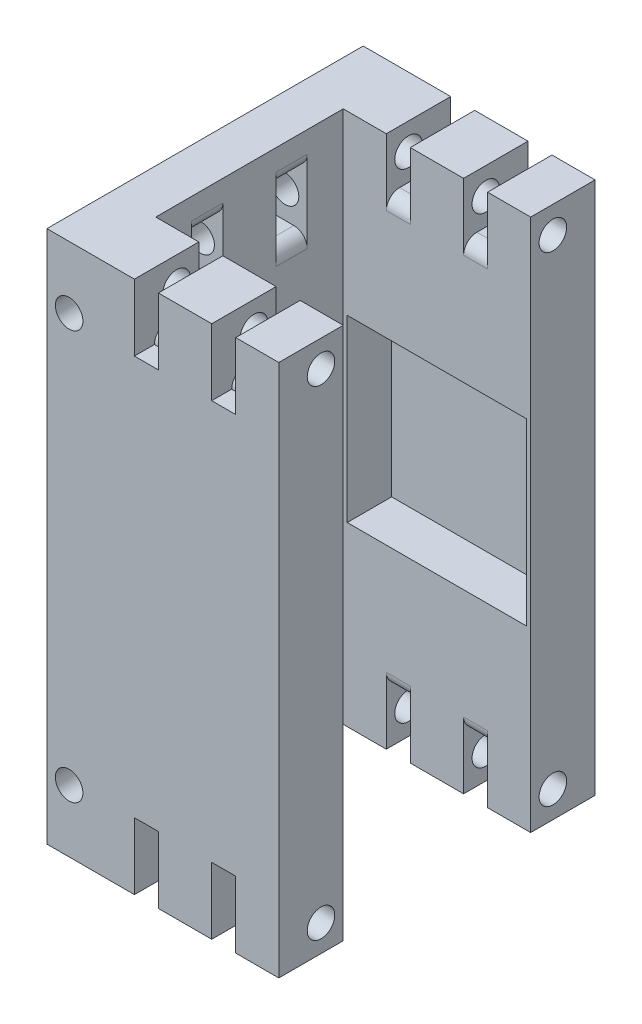
SolidWorks part; units mm, degrees
material "C (石墨)"
ref_plane "前视基准面" through (0, 0, 0) normal (0, 0, 1) x (1, 0, 0)
ref_plane "上视基准面" through (0, 0, 0) normal (0, 1, 0) x (1, 0, 0)
ref_plane "右视基准面" through (0, 0, 0) normal (1, 0, 0) x (0, 0, -1)
other "Configuration Table"
sketch "草图1" plane through (0, 0, 0) normal (0, 1, 0) x (1, 0, 0)
  line L0 (-5, -5) -> (26.1, -5)
  line L1 (0, 0) -> (21.1, 0)
  line L2 (0, 0) -> (0, 21.1)
  line L3 (0, 21.1) -> (21.1, 21.1)
  line L4 (21.1, 0) -> (21.1, 21.1)
  line L5 (26.1, -5) -> (26.1, 26.1)
  line L6 (-5, 26.1) -> (26.1, 26.1)
  line L7 (-5, -5) -> (-5, 26.1)
  dimension "D1" = 21.1
  dimension "D2" = 21.1
  dimension "D3" = 5
extrude "凸台-拉伸1" add sketch "草图1" along normal blind 60
sketch "草图2" plane through (-5, 0, 0) normal (-1, 0, 0) x (0, 0, 1)
  line L0 (-26.1, 60) -> (-26.1, 0) construction
  line L1 (-21.1, 60) -> (-21.1, 0) construction
  line L2 (-26.1, 60) -> (-26.1, 0) construction
  line L3 (-21.1, 60) -> (-21.1, 0) construction
  line L4 (-23.6, 60) -> (-23.6, 0) construction
  line L5 (-26.1, 60) -> (5, 60) construction
  line L6 (-26.1, 0) -> (5, 0) construction
  line L7 (-10.55, 60) -> (-10.55, 0) construction
  circle A0 centre (-23.6, 57) radius 1.55
  circle A1 centre (-23.6, 3) radius 1.55
  circle A2 centre (2.5, 3) radius 1.55
  circle A3 centre (2.5, 57) radius 1.55
  dimension "D4" = 3.1
  dimension "D1" = 2.5
  dimension "D2" = 3
  dimension "D3" = 3
extrude "切除-拉伸1" cut sketch "草图2" against normal through all
sketch "草图3" plane through (0, 0, -21.1) normal (0, 0, 1) x (1, 0, 0)
  line L0 (10.55, 60) -> (10.55, 0) construction
  line L1 (26.1, 30) -> (-5, 30) construction
  line L2 (4.85, 60) -> (7.55, 60)
  line L3 (4.85, 60) -> (4.85, 54)
  line L4 (0, 0) -> (21.1, 0)
  line L5 (21.1, 0) -> (21.1, 60)
  line L6 (21.1, 60) -> (0, 60)
  line L7 (0, 60) -> (0, 0)
  line L8 (0, 0) -> (21.1, 0) construction
  line L9 (21.1, 0) -> (21.1, 60) construction
  line L10 (21.1, 60) -> (0, 60) construction
  line L11 (0, 60) -> (0, 0) construction
  line L12 (4.85, 54) -> (7.55, 54)
  line L13 (7.55, 60) -> (7.55, 54)
  line L14 (13.55, 60) -> (16.25, 60)
  line L15 (13.55, 60) -> (13.55, 54)
  line L16 (13.55, 54) -> (16.25, 54)
  line L17 (16.25, 60) -> (16.25, 54)
  line L18 (26.1, 60) -> (26.1, 0) construction
  line L19 (-5, 60) -> (-5, 0) construction
  line L20 (16.25, 0) -> (16.25, 6)
  line L21 (13.55, 6) -> (16.25, 6)
  line L22 (13.55, 0) -> (13.55, 6)
  line L23 (13.55, 0) -> (16.25, 0)
  line L24 (7.55, 0) -> (7.55, 6)
  line L25 (4.85, 6) -> (7.55, 6)
  line L26 (4.85, 0) -> (4.85, 6)
  line L27 (4.85, 0) -> (7.55, 0)
  dimension "D2" = 6
  dimension "D3" = 2.7
  dimension "D4" = 3
  dimension "D1" = 0
extrude "切除-拉伸2" cut sketch "草图3" against normal through all and the other way through all
sketch "草图4" plane through (0, 0, -26.1) normal (0, 0, -1) x (-1, 0, 0)
  line L0 (-23.6, 60) -> (-23.6, 0) construction
  line L1 (-26.1, 60) -> (-16.25, 60) construction
  line L2 (-26.1, 0) -> (-16.25, 0) construction
  line L3 (-26.1, 60) -> (-26.1, 0) construction
  line L4 (-26.1, 30) -> (5, 30) construction
  line L5 (5, 60) -> (5, 0) construction
  line L6 (-10.55, 60) -> (-10.55, 0) construction
  line L7 (-13.55, 60) -> (-7.55, 60) construction
  line L8 (-13.55, 0) -> (-7.55, 0) construction
  circle A0 centre (-23.6, 53) radius 1.55
  circle A1 centre (2.5, 53) radius 1.55
  circle A2 centre (2.5, 7) radius 1.55
  circle A3 centre (-23.6, 7) radius 1.55
  dimension "D2" = 3.1
  dimension "D1" = 2.5
  dimension "D3" = 7
extrude "切除-拉伸3" cut sketch "草图4" against normal through all
sketch "草图5" plane through (21.1, 0, 0) normal (-1, 0, 0) x (0, 0, 1)
  line L0 (-10.55, 60) -> (-10.55, 0) construction
  line L1 (-26.1, 60) -> (5, 60) construction
  line L2 (-26.1, 0) -> (5, 0) construction
  line L3 (-26.1, 53) -> (5, 53) construction
  line L4 (-26.1, 60) -> (-26.1, 0) construction
  line L5 (5, 60) -> (5, 0) construction
  line L6 (5, 30) -> (-26.1, 30) construction
  line L7 (-17.05, 56.1) -> (-13.55, 56.1)
  line L8 (-17.05, 56.1) -> (-17.05, 49.9)
  line L9 (-17.05, 49.9) -> (-13.55, 49.9)
  line L10 (-13.55, 56.1) -> (-13.55, 49.9)
  line L11 (-7.55, 56.1) -> (-4.05, 56.1)
  line L12 (-7.55, 56.1) -> (-7.55, 49.9)
  line L13 (-7.55, 49.9) -> (-4.05, 49.9)
  line L14 (-4.05, 56.1) -> (-4.05, 49.9)
  line L15 (-4.05, 3.9) -> (-4.05, 10.1)
  line L16 (-7.55, 10.1) -> (-4.05, 10.1)
  line L17 (-7.55, 3.9) -> (-7.55, 10.1)
  line L18 (-7.55, 3.9) -> (-4.05, 3.9)
  line L19 (-13.55, 3.9) -> (-13.55, 10.1)
  line L20 (-17.05, 10.1) -> (-13.55, 10.1)
  line L21 (-17.05, 3.9) -> (-17.05, 10.1)
  line L22 (-17.05, 3.9) -> (-13.55, 3.9)
  dimension "D1" = 7
  dimension "D2" = 3
  dimension "D3" = 3.5
  dimension "D4" = 6.2
  dimension "D5" = 6.2
extrude "切除-拉伸4" cut sketch "草图5" against normal through all and the other way through all
ref_plane "基准面1" through (0, 30, 0) normal (0, 1, 0) x (1, 0, 0)
fillet "圆角1" radius 1.5 48 edges at (14.9, 6, 0) (14.9, 6, 5) (6.2, 6, 0) (6.2, 6, 5) (6.2, 6, -21.1) (6.2, 6, -26.1) (14.9, 6, -21.1) (14.9, 6, -26.1) (21.1, 10.1, -15.3) (21.1, 10.1, -5.8) (26.1, 10.1, -15.3) (26.1, 10.1, -5.8) (26.1, 3.9, -15.3) (21.1, 3.9, -15.3) (26.1, 3.9, -5.8) (21.1, 3.9, -5.8) (0, 10.1, -5.8) (0, 10.1, -15.3) (-5, 10.1, -5.8) (-5, 10.1, -15.3) (-5, 3.9, -5.8) (0, 3.9, -5.8) (0, 3.9, -15.3) (-5, 3.9, -15.3) (21.1, 56.1, -5.8) (26.1, 56.1, -5.8) (0, 56.1, -5.8) (0, 56.1, -15.3) (-5, 56.1, -5.8) (-5, 56.1, -15.3) (0, 49.9, -5.8) (0, 49.9, -15.3) (-5, 49.9, -5.8) (-5, 49.9, -15.3) (6.2, 54, -21.1) (14.9, 54, -21.1) (6.2, 54, -26.1) (14.9, 54, -26.1) (26.1, 56.1, -15.3) (21.1, 56.1, -15.3) (21.1, 49.9, -15.3) (21.1, 49.9, -5.8) (26.1, 49.9, -5.8) (14.9, 54, 5) (6.2, 54, 0) (14.9, 54, 0) (6.2, 54, 5) (26.1, 49.9, -15.3)
sketch "草图6" plane through (0, 0, 5) normal (0, 0, 1) x (1, 0, 0)
  line L0 (5.4175, 30) -> (-5.4175, 30) construction
  line L1 (0.45, 40.1) -> (20.65, 40.1)
  line L2 (0.45, 40.1) -> (0.45, 19.9)
  line L3 (0.45, 19.9) -> (20.65, 19.9)
  line L4 (20.65, 40.1) -> (20.65, 19.9)
  line L5 (0.45, 40.1) -> (20.65, 19.9) construction
  line L6 (0.45, 19.9) -> (20.65, 40.1) construction
  line L7 (10.55, 30) -> (26.2189, 30) construction
  line L8 (26.2189, 30) -> (24.6313, 30)
  line L9 (10.55, 30) -> (10.55, 60) construction
  line L10 (7.55, 60) -> (13.55, 60) construction
  point P0 (10.55, 30)
  dimension "D1" = 20.2
  dimension "D2" = 20.2
extrude "切除-拉伸5" cut sketch "草图6" against normal through all contours L4 L1 L2 L3
sketch "草图7" plane through (0, 0, 5) normal (0, 0, 1) x (1, 0, 0)
  line L20 (13.55, 0) -> (13.55, 7.5)
  line L21 (13.55, 7.5) -> (16.25, 7.5)
  line L22 (16.25, 7.5) -> (16.25, 0)
  line L23 (16.25, 0) -> (26.1, 0)
  line L24 (26.1, 0) -> (26.1, 60)
  line L25 (26.1, 60) -> (16.25, 60)
  line L26 (16.25, 60) -> (16.25, 52.5)
  line L27 (16.25, 52.5) -> (13.55, 52.5)
  line L28 (13.55, 52.5) -> (13.55, 60)
  line L29 (13.55, 60) -> (7.55, 60)
  line L30 (7.55, 60) -> (7.55, 52.5)
  line L31 (7.55, 52.5) -> (4.85, 52.5)
  line L32 (4.85, 52.5) -> (4.85, 60)
  line L33 (4.85, 60) -> (-5, 60)
  line L34 (-5, 60) -> (-5, 0)
  line L35 (-5, 0) -> (4.85, 0)
  line L36 (4.85, 0) -> (4.85, 7.5)
  line L37 (4.85, 7.5) -> (7.55, 7.5)
  line L38 (7.55, 7.5) -> (7.55, 0)
  line L39 (7.55, 0) -> (13.55, 0)
  line L40 (13.55, 0) -> (13.55, 7.5)
  line L41 (13.55, 7.5) -> (16.25, 7.5)
  line L42 (16.25, 7.5) -> (16.25, 0)
  line L43 (16.25, 0) -> (26.1, 0)
  line L44 (26.1, 0) -> (26.1, 60)
  line L45 (26.1, 60) -> (16.25, 60)
  line L46 (16.25, 60) -> (16.25, 52.5)
  line L47 (16.25, 52.5) -> (13.55, 52.5)
  line L48 (13.55, 52.5) -> (13.55, 60)
  line L49 (13.55, 60) -> (7.55, 60)
  line L50 (7.55, 60) -> (7.55, 52.5)
  line L51 (7.55, 52.5) -> (4.85, 52.5)
  line L52 (4.85, 52.5) -> (4.85, 60)
  line L53 (4.85, 60) -> (-5, 60)
  line L54 (-5, 60) -> (-5, 0)
  line L55 (-5, 0) -> (4.85, 0)
  line L56 (4.85, 0) -> (4.85, 7.5)
  line L57 (4.85, 7.5) -> (7.55, 7.5)
  line L58 (7.55, 7.5) -> (7.55, 0)
  line L59 (7.55, 0) -> (13.55, 0)
  circle A0 centre (23.6, 7) radius 1.55 construction
  circle A1 centre (23.6, 53) radius 1.55 construction
  circle A2 centre (-2.5, 53) radius 1.55 construction
  circle A3 centre (-2.5, 7) radius 1.55 construction
  circle A4 centre (23.6, 7) radius 1.55
  circle A5 centre (23.6, 53) radius 1.55
  circle A6 centre (-2.5, 53) radius 1.55
  circle A7 centre (-2.5, 7) radius 1.55
  dimension "D1" = 0
sketch "草图8" plane through (0, 0, -26.1) normal (0, 0, -1) x (-1, 0, 0)
  line L20 (-7.55, 7.5) -> (-4.85, 7.5)
  line L21 (-4.85, 7.5) -> (-4.85, 0)
  line L22 (-4.85, 0) -> (5, 0)
  line L23 (5, 0) -> (5, 60)
  line L24 (5, 60) -> (-4.85, 60)
  line L25 (-4.85, 60) -> (-4.85, 52.5)
  line L26 (-4.85, 52.5) -> (-7.55, 52.5)
  line L27 (-7.55, 52.5) -> (-7.55, 60)
  line L28 (-7.55, 60) -> (-13.55, 60)
  line L29 (-13.55, 60) -> (-13.55, 52.5)
  line L30 (-13.55, 52.5) -> (-16.25, 52.5)
  line L31 (-16.25, 52.5) -> (-16.25, 60)
  line L32 (-16.25, 60) -> (-26.1, 60)
  line L33 (-26.1, 60) -> (-26.1, 0)
  line L34 (-26.1, 0) -> (-16.25, 0)
  line L35 (-16.25, 0) -> (-16.25, 7.5)
  line L36 (-16.25, 7.5) -> (-13.55, 7.5)
  line L37 (-13.55, 7.5) -> (-13.55, 0)
  line L38 (-13.55, 0) -> (-7.55, 0)
  line L39 (-7.55, 0) -> (-7.55, 7.5)
  line L40 (-7.55, 7.5) -> (-4.85, 7.5)
  line L41 (-4.85, 7.5) -> (-4.85, 0)
  line L42 (-4.85, 0) -> (5, 0)
  line L43 (5, 0) -> (5, 60)
  line L44 (5, 60) -> (-4.85, 60)
  line L45 (-4.85, 60) -> (-4.85, 52.5)
  line L46 (-4.85, 52.5) -> (-7.55, 52.5)
  line L47 (-7.55, 52.5) -> (-7.55, 60)
  line L48 (-7.55, 60) -> (-13.55, 60)
  line L49 (-13.55, 60) -> (-13.55, 52.5)
  line L50 (-13.55, 52.5) -> (-16.25, 52.5)
  line L51 (-16.25, 52.5) -> (-16.25, 60)
  line L52 (-16.25, 60) -> (-26.1, 60)
  line L53 (-26.1, 60) -> (-26.1, 0)
  line L54 (-26.1, 0) -> (-16.25, 0)
  line L55 (-16.25, 0) -> (-16.25, 7.5)
  line L56 (-16.25, 7.5) -> (-13.55, 7.5)
  line L57 (-13.55, 7.5) -> (-13.55, 0)
  line L58 (-13.55, 0) -> (-7.55, 0)
  line L59 (-7.55, 0) -> (-7.55, 7.5)
  circle A0 centre (-23.6, 7) radius 1.55 construction
  circle A1 centre (2.5, 7) radius 1.55 construction
  circle A2 centre (2.5, 53) radius 1.55 construction
  circle A3 centre (-23.6, 53) radius 1.55 construction
  circle A4 centre (-23.6, 7) radius 1.55
  circle A5 centre (2.5, 7) radius 1.55
  circle A6 centre (2.5, 53) radius 1.55
  circle A7 centre (-23.6, 53) radius 1.55
  dimension "D1" = 0
extrude "凸台-拉伸2" add sketch "草图7" along normal blind 2.25
extrude "凸台-拉伸3" add sketch "草图8" along normal blind 2.25
sketch "草图9" plane through (0, 0, -28.35) normal (0, 0, -1) x (-1, 0, 0)
  line L0 (-21.1, 60) -> (-21.1, 0) construction
  line L1 (-21.1, 60) -> (-21.1, 0) construction
  line L2 (-21.1, 60) -> (-26.1, 60)
  line L3 (-26.1, 60) -> (-26.1, 0)
  line L4 (-26.1, 0) -> (-21.1, 0)
  line L5 (-21.1, 0) -> (-21.1, 60)
extrude "切除-拉伸6" cut sketch "草图9" against normal through all
